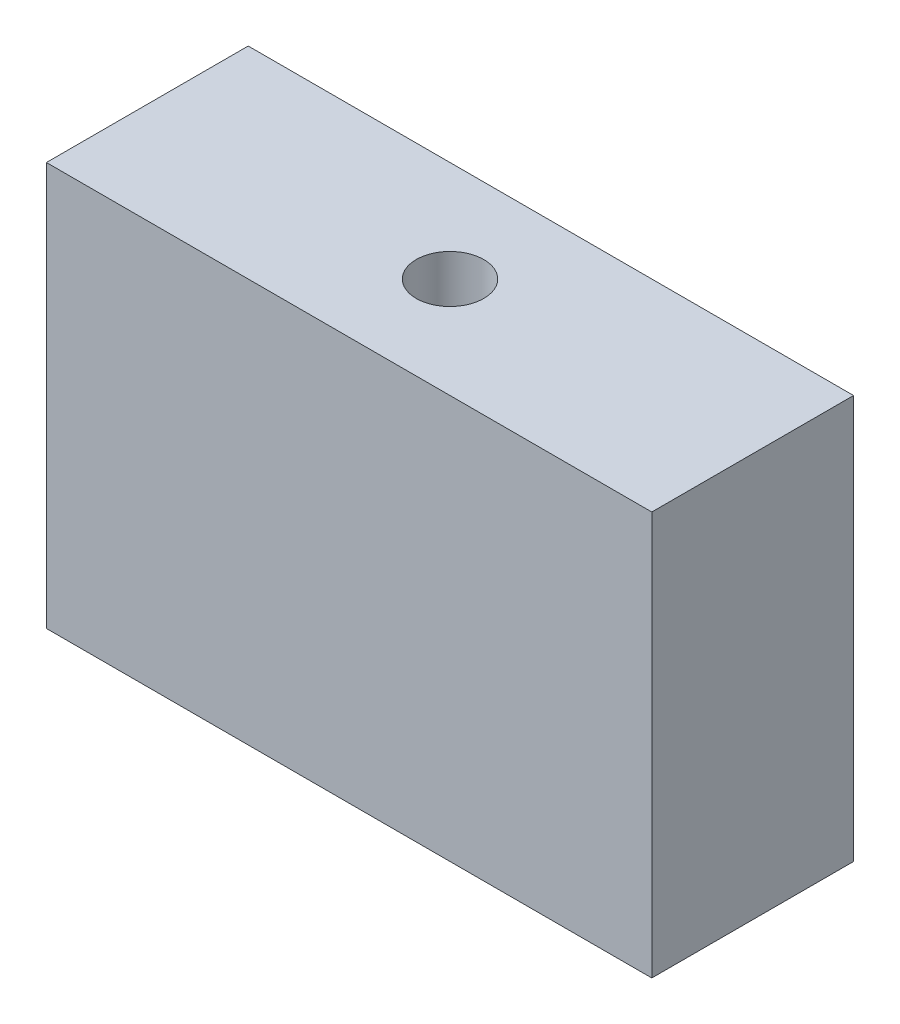
SolidWorks part; units mm, degrees
ref_plane "Front Plane" through (0, 0, 0) normal (0, 0, 1) x (1, 0, 0)
ref_plane "Top Plane" through (0, 0, 0) normal (0, 1, 0) x (1, 0, 0)
ref_plane "Right Plane" through (0, 0, 0) normal (1, 0, 0) x (0, 0, -1)
sketch "Sketch1" plane through (0, 0, 0) normal (0, 1, 0) x (1, 0, 0)
  line L1 (38.1, -12.7) -> (-38.1, -12.7)
  line L2 (38.1, -12.7) -> (38.1, 12.7)
  line L3 (38.1, 12.7) -> (-38.1, 12.7)
  line L4 (-38.1, -12.7) -> (-38.1, 12.7)
  line L5 (38.1, -12.7) -> (-38.1, 12.7) construction
  line L6 (38.1, 12.7) -> (-38.1, -12.7) construction
  circle A0 centre (0, 0) radius 4.25
  point P0 (0, 0)
  dimension "D3" = 8.5
  dimension "D1" = 76.2
  dimension "D2" = 25.4
extrude "Boss-Extrude1" add sketch "Sketch1" along normal mid plane 50.8
